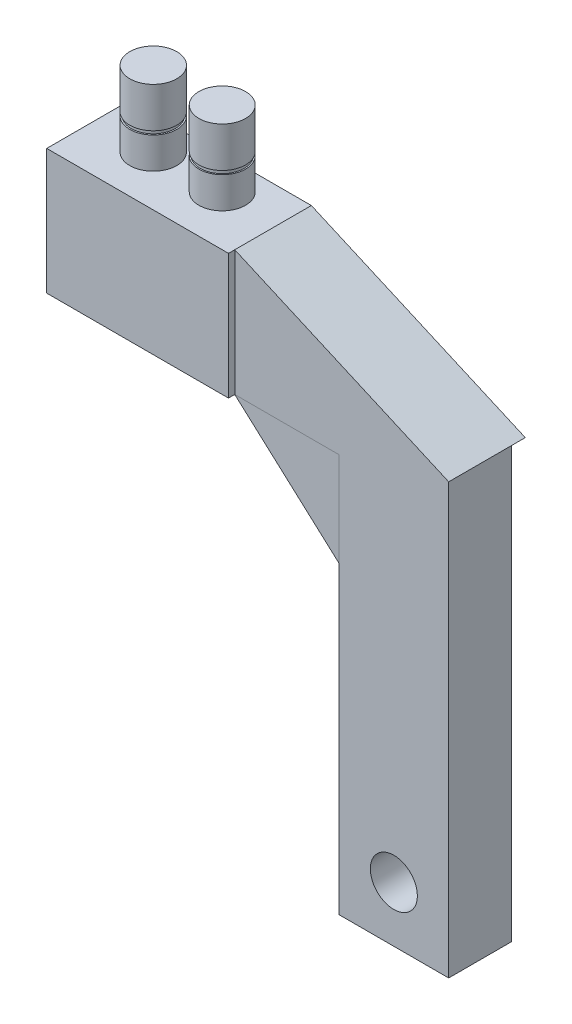
SolidWorks part; units mm, degrees
ref_plane "Front Plane" through (0, 0, 0) normal (0, 0, 1) x (1, 0, 0)
ref_plane "Top Plane" through (0, 0, 0) normal (0, 1, 0) x (1, 0, 0)
ref_plane "Right Plane" through (0, 0, 0) normal (1, 0, 0) x (0, 0, -1)
sketch "Sketch1" plane through (0, 0, 0) normal (0, 1, 0) x (1, 0, 0)
  line L1 (18.415, -10.16) -> (-18.415, -10.16)
  line L2 (18.415, -10.16) -> (18.415, 10.16)
  line L3 (18.415, 10.16) -> (-18.415, 10.16)
  line L4 (-18.415, -10.16) -> (-18.415, 10.16)
  line L5 (18.415, -10.16) -> (-18.415, 10.16) construction
  line L6 (18.415, 10.16) -> (-18.415, -10.16) construction
  point P0 (0, 0)
  dimension "D1" = 36.83
  dimension "D2" = 20.32
extrude "Boss-Extrude1" add sketch "Sketch1" against normal blind 25.4
sketch "Sketch2" plane through (18.415, 0, 0) normal (1, 0, 0) x (0, 0, -1)
  line L0 (-10.16, -25.4) -> (10.16, -25.4) construction
  line L1 (-8.89, -25.4) -> (3.81, -25.4)
  line L2 (-8.89, -25.4) -> (-8.89, -19.05)
  line L3 (-8.89, -19.05) -> (3.81, -19.05)
  line L4 (3.81, -25.4) -> (3.81, -19.05)
  line L5 (-10.16, -25.4) -> (-10.16, 0) construction
  dimension "D1" = 12.7
  dimension "D2" = 6.35
  dimension "D3" = 1.27
extrude "Boss-Extrude2" add sketch "Sketch2" along normal blind 43.3442
sketch "Sketch3" plane through (0, -25.4, 0) normal (0, -1, 0) x (-1, 0, 0)
  line L0 (-61.7592, 3.81) -> (-18.415, 3.81) construction
  line L1 (-61.7592, -8.89) -> (-39.5342, -8.89)
  line L2 (-61.7592, -8.89) -> (-61.7592, 3.81)
  line L3 (-61.7592, 3.81) -> (-39.5342, 3.81)
  line L4 (-39.5342, -8.89) -> (-39.5342, 3.81)
  dimension "D1" = 22.225
extrude "Boss-Extrude3" add sketch "Sketch3" along normal blind 80.7135
sketch "Sketch4" plane through (0, 0, 8.89) normal (0, 0, 1) x (1, 0, 0)
  line L0 (61.7592, -106.1135) -> (39.5342, -106.1135) construction
  line L1 (39.5342, -106.1135) -> (39.5342, -25.4) construction
  circle A0 centre (50.6467, -94.8842) radius 4.7625
  dimension "D1" = 11.2293
  dimension "D2" = 9.525
  dimension "D3" = 11.1125
extrude "Cut-Extrude1" cut sketch "Sketch4" against normal through all
sketch "Sketch5" plane through (0, 0, 0) normal (0, 1, 0) x (1, 0, 0)
  line L0 (-18.415, 10.16) -> (-18.415, -10.16) construction
  line L1 (18.415, 10.16) -> (-18.415, 10.16) construction
  line L2 (18.415, -10.16) -> (18.415, 10.16) construction
  circle A0 centre (-6.985, 0) radius 4.7625
  circle A1 centre (6.985, 0) radius 4.7294
  dimension "D1" = 11.43
  dimension "D3" = 9.525
  dimension "D5" = 9.4588
  dimension "D2" = 10.16
  dimension "D4" = 11.43
  dimension "D6" = 10.16
extrude "Boss-Extrude4" add sketch "Sketch5" along normal blind 15.24
sketch "Sketch7" plane through (0, 0, 10.16) normal (0, 0, 1) x (1, 0, 0)
  line L0 (18.415, 0) -> (61.7592, -19.05)
  line L1 (61.7592, -19.05) -> (18.415, -19.05)
  line L2 (18.415, -25.4) -> (18.415, 0) construction
  line L3 (18.415, -19.05) -> (18.415, 0)
extrude "Boss-Extrude5" add sketch "Sketch7" against normal blind 20.32
sketch "Sketch8" plane through (0, -19.05, 0) normal (0, -1, 0) x (-1, 0, 0)
  line L1 (-61.7592, -10.16) -> (-18.415, -10.16)
  line L2 (-61.7592, -10.16) -> (-61.7592, -8.89)
  line L3 (-61.7592, -8.89) -> (-18.415, -8.89)
  line L4 (-18.415, -10.16) -> (-18.415, -8.89)
extrude "Cut-Extrude2" cut sketch "Sketch8" against normal through all contours L2 L1 L4 L3
sketch "Sketch13" plane through (0, 0, 8.89) normal (0, 0, 1) x (1, 0, 0)
  line L0 (18.415, -25.4) -> (39.5342, -25.4)
  line L1 (39.5342, -25.4) -> (39.5342, -44.45)
  line L2 (39.5342, -44.45) -> (18.415, -25.4)
  line L3 (39.5342, -25.4) -> (18.415, -25.4) construction
  line L4 (39.5342, -106.1135) -> (39.5342, -25.4) construction
  dimension "D1" = 0
  dimension "D2" = 0
  dimension "D3" = 19.05
extrude "Boss-Extrude10" add sketch "Sketch13" against normal blind 20.32 separate body
sketch3d "3DSketch3"
  circle A0 centre (-6.985, 6.35, 0) radius 5.08
  circle A1 centre (6.985, 6.35, 0) radius 5.08
  circle A2 centre (-6.985, 15.24, 0) radius 4.7625 construction
  circle A3 centre (6.985, 15.24, 0) radius 4.7294 construction
  point P2 (-6.985, 11.43, 0)
  point P5 (6.985, 11.43, 0)
  point P9 (-6.985, 20.0025, 0)
  point P13 (6.985, 19.9694, 0)
  dimension "D2" = 10.16
  dimension "D3" = 10.16
  dimension "D1" = 6.35
extrude "Cut-Extrude4" cut sketch "3DSketch3" along direction (0, 1, 0) on the side against the normal blind 0.7366
sketch "Sketch14" plane through (0, 6.35, 0) normal (0, 1, 0) x (1, 0, 0)
  circle A0 centre (-6.985, 0) radius 4.4704
  circle A1 centre (6.985, 0) radius 4.4704
  dimension "D1" = 8.9408
  dimension "D2" = 8.9408
extrude "Boss-Extrude11" add sketch "Sketch14" along normal up to surface (0.7366 mm away) up to face at (-6.985, 7.0866, 4.7625)
sketch "Sketch16" plane through (0, 0, -11.43) normal (0, 0, -1) x (-1, 0, 0)
  line L0 (-18.415, 0) -> (18.415, 0) construction
  line L1 (80.3407, -137.2609) -> (-137.0111, -137.2609)
  line L2 (80.3407, -137.2609) -> (80.3407, 74.0982)
  line L3 (80.3407, 74.0982) -> (-137.0111, 74.0982)
  line L4 (-137.0111, -137.2609) -> (-137.0111, 74.0982)
  line L5 (80.3407, -137.2609) -> (-137.0111, 74.0982) construction
  line L6 (80.3407, 74.0982) -> (-137.0111, -137.2609) construction
  point P0 (-28.3352, -31.5814)
  point P7 (0, 0)
  dimension "D1" = 217.3519
  dimension "D2" = 211.3591
  dimension "D3" = 137.2609
  dimension "D4" = 80.3407
extrude "Cut-Extrude5" cut sketch "Sketch16" against normal blind 4.8028
